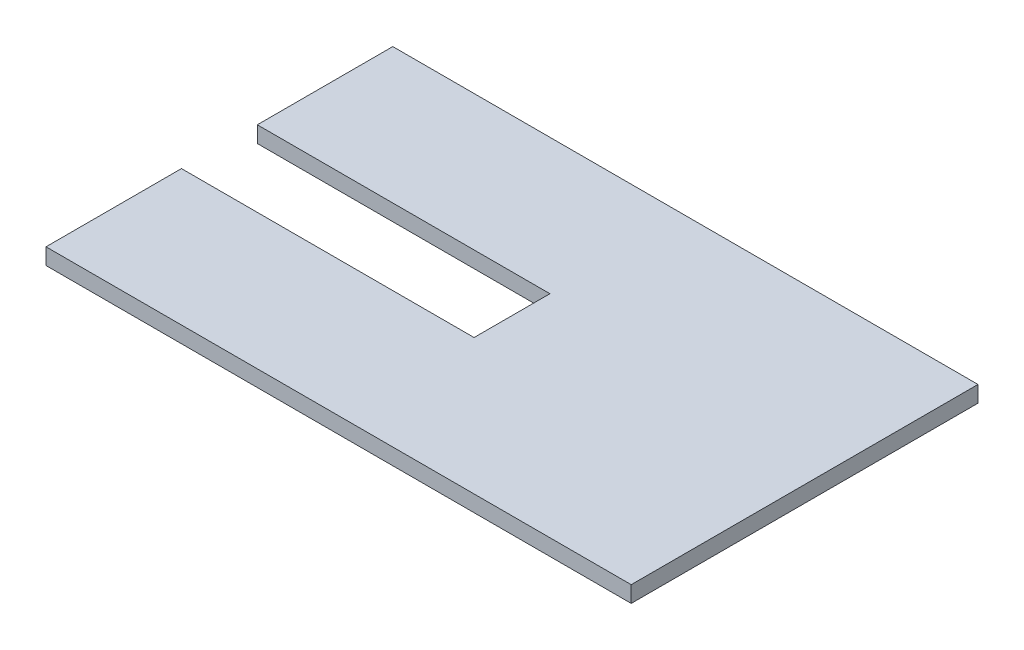
SolidWorks part; units mm, degrees
ref_plane "Alzado" through (0, 0, 0) normal (0, 0, 1) x (1, 0, 0)
ref_plane "Planta" through (0, 0, 0) normal (0, 1, 0) x (1, 0, 0)
ref_plane "Vista lateral" through (0, 0, 0) normal (1, 0, 0) x (0, 0, -1)
sketch "Croquis1" plane through (0, 0, 0) normal (0, 1, 0) x (1, 0, 0)
  line L0 (0, -55) -> (0, 55) construction
  line L1 (-54, -32) -> (54, -32)
  line L2 (-54, -32) -> (-54, -7)
  line L3 (-54, 32) -> (54, 32)
  line L4 (54, -32) -> (54, 32)
  line L5 (-55, 0) -> (55, 0) construction
  line L6 (-54, 7) -> (0, 7)
  line L7 (0, 7) -> (0, -7)
  line L8 (-54, -7) -> (0, -7)
  line L9 (-54, 7) -> (-54, 32)
  point P0 (0, 0)
  point P14 (0, 0)
  dimension "D1" = 108
  dimension "D2" = 64
  dimension "D3" = 54
  dimension "D4" = 32
  dimension "D5" = 7
extrude "Saliente-Extruir1" add sketch "Croquis1" along normal blind 3
